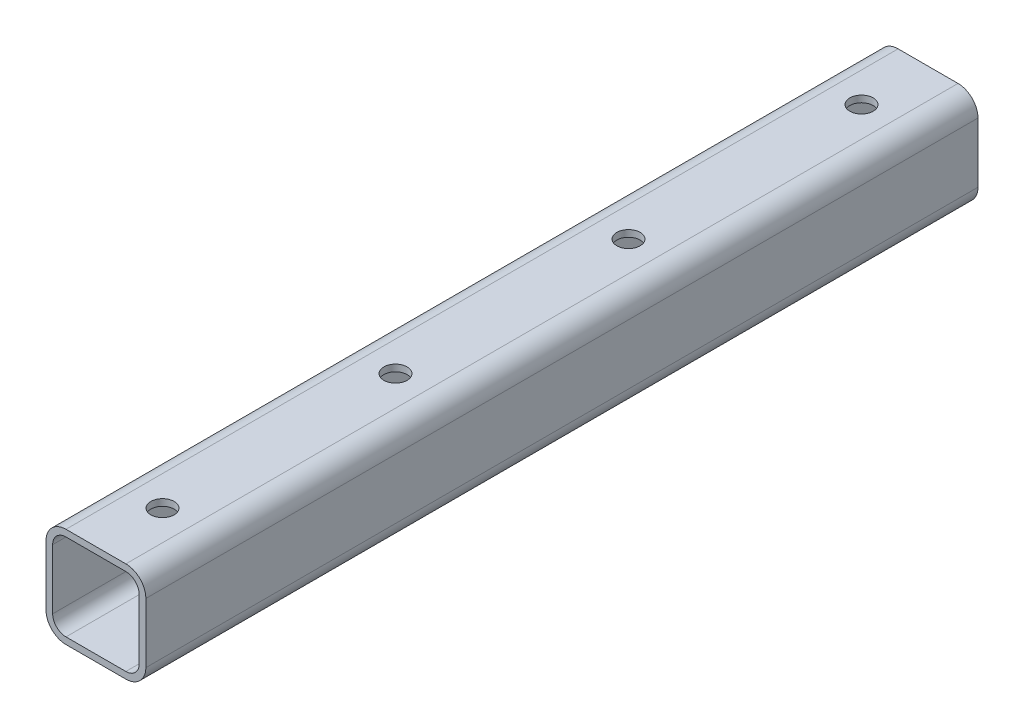
SolidWorks part; units mm, degrees
material "1.0038 (S235JRG2)"
ref_plane "Ebene vorne" through (0, 0, 0) normal (0, 0, 1) x (1, 0, 0)
ref_plane "Ebene oben" through (0, 0, 0) normal (0, 1, 0) x (1, 0, 0)
ref_plane "Ebene rechts" through (0, 0, 0) normal (1, 0, 0) x (0, 0, -1)
sketch "Skizze1" plane through (0, 0, 0) normal (0, 0, 1) x (1, 0, 0)
  line L0 (0, 0) -> (0, 67.8952) construction
  line L1 (-9, 15) -> (9, 15)
  line L2 (0, 0) -> (65.406, 0) construction
  line L3 (15, 9) -> (15, -9)
  line L4 (-15, 9) -> (-15, -9)
  line L5 (-9, -15) -> (9, -15)
  line L6 (-13, 9) -> (-13, -9)
  line L7 (-9, -13) -> (9, -13)
  line L8 (13, 9) -> (13, -9)
  line L9 (-9, 13) -> (9, 13)
  arc A0 (9, 15) -> (15, 9) centre (9, 9) cw
  arc A1 (-9, 15) -> (-15, 9) centre (-9, 9) ccw
  arc A2 (-9, -15) -> (-15, -9) centre (-9, -9) cw
  arc A3 (9, -15) -> (15, -9) centre (9, -9) ccw
  arc A4 (-9, -13) -> (-13, -9) centre (-9, -9) cw
  arc A5 (9, -13) -> (13, -9) centre (9, -9) ccw
  arc A6 (9, 13) -> (13, 9) centre (9, 9) cw
  arc A7 (-9, 13) -> (-13, 9) centre (-9, 9) ccw
  point P12 (15, 0)
  point P13 (0, 15)
  point P19 (-15, 0)
  dimension "D1" = 6
  dimension "D3" = 30
  dimension "D4" = 30
  dimension "D2" = 2
extrude "Aufsatz-Linear austragen1" add sketch "Skizze1" along normal mid plane 250
sketch "Skizze2" plane through (0, 15, 0) normal (0, 1, 0) x (1, 0, 0)
  line L0 (0, 0) -> (35.9621, 0) construction
  line L1 (0, 0) -> (0, 132.8182) construction
  circle A0 centre (0, 105) radius 3.5
  circle A1 centre (0, 35) radius 3.5
  circle A4 centre (0, -35) radius 3.5
  circle A5 centre (0, -105) radius 3.5
  dimension "D1" = 7
  dimension "D3" = 70
  dimension "D2" = 70
extrude "Schnitt-Linear austragen1" cut sketch "Skizze2" against normal blind 60
